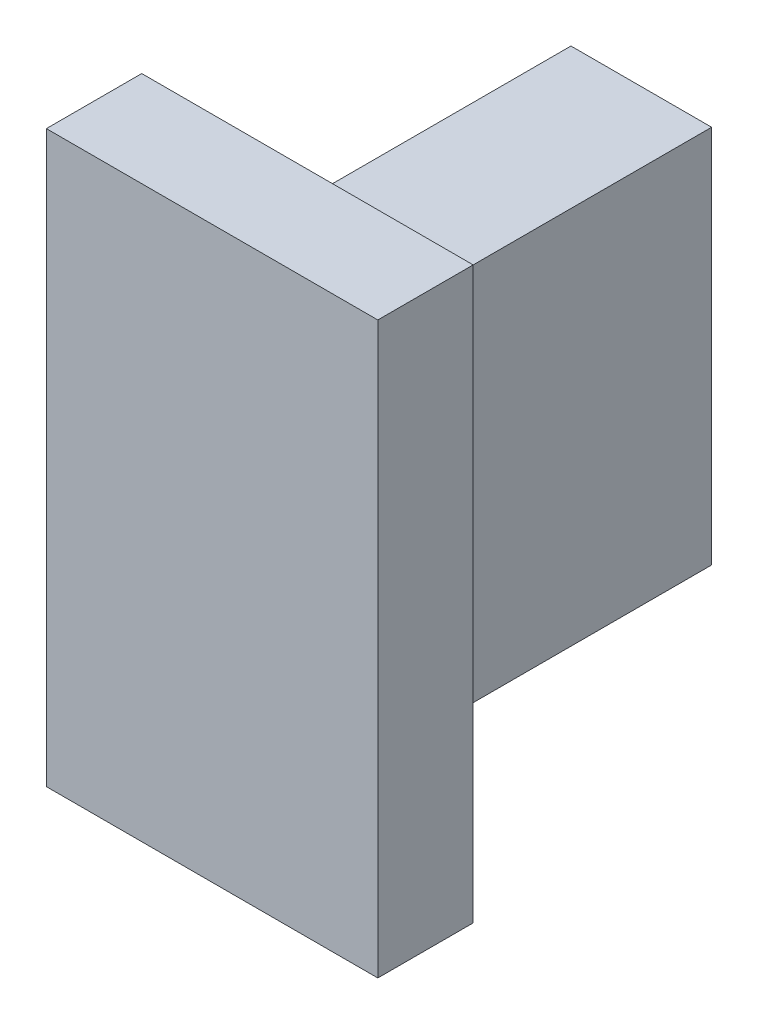
SolidWorks part; units mm, degrees
ref_plane "Front Plane" through (0, 0, 0) normal (0, 0, 1) x (1, 0, 0)
ref_plane "Top Plane" through (0, 0, 0) normal (0, 1, 0) x (1, 0, 0)
ref_plane "Right Plane" through (0, 0, 0) normal (1, 0, 0) x (0, 0, -1)
sketch "Sketch1" plane through (0, 0, 0) normal (0, 0, 1) x (1, 0, 0)
  line L1 (-1.0316, 1.2332) -> (1.9184, 1.2332)
  line L2 (-1.0316, 1.2332) -> (-1.0316, -6.7168)
  line L3 (-1.0316, -6.7168) -> (1.9184, -6.7168)
  line L4 (1.9184, 1.2332) -> (1.9184, -6.7168)
  dimension "D1" = 2.95
  dimension "D2" = 7.95
extrude "Boss-Extrude1" add sketch "Sketch1" along normal blind 8
shell "Shell1" thickness 0.5
sketch "Sketch2" plane through (0, 0, 8) normal (0, 0, 1) x (1, 0, 0)
  line L0 (1.9184, 1.2332) -> (-1.0316, 1.2332) construction
  line L1 (-2.0316, 2.2332) -> (2.9184, 2.2332)
  line L2 (-2.0316, 2.2332) -> (-2.0316, -7.7168)
  line L3 (-2.0316, -7.7168) -> (2.9184, -7.7168)
  line L4 (2.9184, 2.2332) -> (2.9184, -7.7168)
  line L5 (-1.0316, -6.7168) -> (1.9184, -6.7168) construction
  line L6 (1.9184, -6.7168) -> (1.9184, 1.2332) construction
  line L7 (-1.0316, 1.2332) -> (-1.0316, -6.7168) construction
  dimension "D1" = 1
  dimension "D2" = 1
  dimension "D3" = 1
  dimension "D4" = 1
extrude "Boss-Extrude2" add sketch "Sketch2" along normal blind 1
sketch "Sketch3" plane through (0, 0, 7.5) normal (0, 0, -1) x (-1, 0, 0)
  line L0 (-1.4184, -1.0043) -> (0.5316, -1.0043)
  line L1 (-1.4184, -6.2168) -> (-1.4184, 0.7332) construction
  line L2 (0.5316, 0.7332) -> (0.5316, -6.2168) construction
  line L3 (-1.4184, -2.7443) -> (0.5316, -2.7443)
  line L4 (-1.4184, -4.4843) -> (0.5316, -4.4843)
  line L5 (-1.4184, -0.7043) -> (0.5316, -0.7043)
  line L6 (-1.4184, -6.2168) -> (-1.4184, 0.7332) construction
  line L7 (-1.4184, 0.7332) -> (0.5316, 0.7332) construction
  line L8 (0.5316, 0.7332) -> (0.5316, -6.2168) construction
  line L9 (-1.4184, -2.4443) -> (0.5316, -2.4443)
  line L10 (-1.4184, -4.1843) -> (0.5316, -4.1843)
  line L11 (-1.4184, -0.7043) -> (-1.4184, -1.0043)
  line L12 (0.5316, -0.7043) -> (0.5316, -1.0043)
  line L13 (0.5316, -2.4443) -> (0.5316, -2.7443)
  line L14 (-1.4184, -2.4443) -> (-1.4184, -2.7443)
  line L15 (-1.4184, -4.1843) -> (-1.4184, -4.4843)
  line L16 (0.5316, -4.1843) -> (0.5316, -4.4843)
  dimension "D2" = 1.7375
  dimension "D3" = 1.74
  dimension "D4" = 0.3
  dimension "D1" = 3
  dimension "D5" = 3
extrude "Boss-Extrude3" add sketch "Sketch3" along normal up to surface (7.5 mm away) up to face at (0.4434, -2.7418, 0)
sketch "Sketch4" plane through (0, 0, 9) normal (0, 0, 1) x (1, 0, 0)
  line L0 (2.9184, 2.2332) -> (-2.0316, 2.2332) construction
  line L1 (-3.0316, 3.2332) -> (3.9184, 3.2332)
  line L2 (-3.0316, 3.2332) -> (-3.0316, -8.7168)
  line L3 (-3.0316, -8.7168) -> (3.9184, -8.7168)
  line L4 (3.9184, 3.2332) -> (3.9184, -8.7168)
  line L5 (-2.0316, -7.7168) -> (2.9184, -7.7168) construction
  line L6 (-2.0316, 2.2332) -> (-2.0316, -7.7168) construction
  line L7 (2.9184, -7.7168) -> (2.9184, 2.2332) construction
  line L9 (-2.0316, 2.2332) -> (2.9184, 2.2332)
  line L10 (-2.0316, 2.2332) -> (-2.0316, -7.7168)
  line L11 (-2.0316, -7.7168) -> (2.9184, -7.7168)
  line L12 (2.9184, 2.2332) -> (2.9184, -7.7168)
  dimension "D1" = 1
  dimension "D2" = 1
  dimension "D3" = 1
  dimension "D4" = 1
extrude "Boss-Extrude5" add sketch "Sketch4" against normal blind 2
